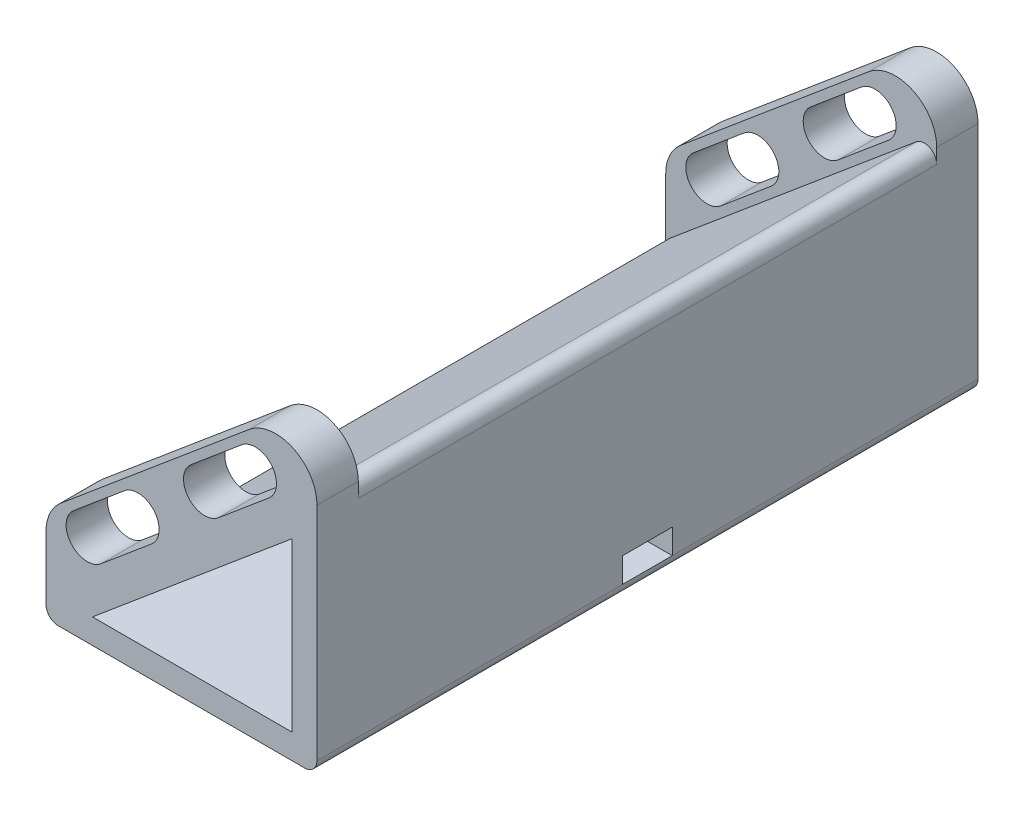
SolidWorks part; units mm, degrees
ref_plane "Front Plane" through (0, 0, 0) normal (0, 0, 1) x (1, 0, 0)
ref_plane "Top Plane" through (0, 0, 0) normal (0, 1, 0) x (1, 0, 0)
ref_plane "Right Plane" through (0, 0, 0) normal (1, 0, 0) x (0, 0, -1)
sketch "Sketch1" plane through (0, 0, 0) normal (0, 0, 1) x (1, 0, 0)
  line L0 (0, 0) -> (29.7938, 25) construction
  line L1 (-0.9642, 1.1491) -> (28.8297, 26.1491)
  line L2 (0.9642, -1.1491) -> (30.758, 23.8509)
  line L3 (0, 0) -> (24.6714, 0) construction
  line L4 (0, 0) -> (29.7938, 0) construction
  line L5 (0, 1.5) -> (29.7938, 1.5)
  line L6 (0, -1.5) -> (29.7938, -1.5)
  line L7 (29.7938, 25) -> (29.7938, 0) construction
  line L8 (31.2938, 25) -> (31.2938, 0)
  line L9 (28.2938, 25) -> (28.2938, 0)
  arc A0 (-0.9642, 1.1491) -> (0.9642, -1.1491) centre (0, 0) ccw
  arc A1 (30.758, 23.8509) -> (28.8297, 26.1491) centre (29.7938, 25) ccw
  arc A2 (0, 1.5) -> (0, -1.5) centre (0, 0) ccw
  arc A3 (29.7938, -1.5) -> (29.7938, 1.5) centre (29.7938, 0) ccw
  arc A4 (31.2938, 25) -> (28.2938, 25) centre (29.7938, 25) ccw
  arc A5 (28.2938, 0) -> (31.2938, 0) centre (29.7938, 0) ccw
  point P3 (14.8969, 12.5)
  point P10 (14.8969, 0)
  point P16 (29.7938, 12.5)
  dimension "D2" = 1.5
  dimension "D1" = 25
  dimension "D3" = 40
extrude "Boss-Extrude1" add sketch "Sketch1" along normal mid plane 80 contours A5 L9 L5 L2 A0 L6 | A4 L1 A2 L5 L2 L9 | A3 L8 A1 L2 L9 L5 | L9 A5 A3 L5 | L5 A2 A0 L2 | A1 A4 L9 L2
sketch "Sketch5" plane through (0, 0, 40) normal (0, 0, 1) x (1, 0, 0)
  line L0 (-1.5, 0) -> (-1.5, 10)
  line L1 (-1.5, 10) -> (31.2938, 37.5173)
  line L2 (31.2938, 37.5173) -> (31.2938, 25)
  line L3 (-0.9642, 1.1491) -> (28.8297, 26.1491) construction
  line L4 (-1.5, 0) -> (31.2938, 25)
  arc A0 (-0.9642, 1.1491) -> (0, -1.5) centre (0, 0) ccw construction
  dimension "D1" = 10
extrude "Boss-Extrude2" add sketch "Sketch5" against normal blind 5
fillet "Fillet1" radius 5 2 edges at (-1.5, 10, 37.5) (31.2938, 37.5173, 37.5)
sketch "Sketch7" plane through (0, 0, 40) normal (0, 0, 1) x (1, 0, 0)
  line L0 (3.5, 9.5452) -> (9.6284, 14.6875) construction
  line L1 (1.853, 11.5081) -> (7.9813, 16.6504)
  line L2 (5.147, 7.5824) -> (11.2754, 12.7247)
  line L3 (4.2744, 14.8453) -> (8.854, 9.3875) construction
  line L4 (-1.5, 7.6685) -> (-1.5, 0)
  line L5 (23.0799, 30.625) -> (0.2861, 11.4987)
  line L6 (31.2938, 25) -> (31.2938, 26.7948)
  line L7 (-0.9642, 1.1491) -> (28.8297, 26.1491)
  line L8 (-1.5, 7.6685) -> (-1.5, 0) construction
  line L9 (23.0799, 30.625) -> (0.2861, 11.4987) construction
  line L10 (31.2938, 25) -> (31.2938, 26.7948) construction
  line L11 (-0.9642, 1.1491) -> (28.8297, 26.1491) construction
  line L12 (3.5, 9.5452) -> (23.8297, 26.6038) construction
  line L13 (13.6648, 18.0745) -> (11.375, 20.8034) construction
  line L14 (23.8297, 26.6038) -> (17.7013, 21.4615) construction
  line L15 (22.1826, 28.5667) -> (16.0543, 23.4244)
  line L16 (25.4767, 24.641) -> (19.3483, 19.4987)
  arc A0 (1.853, 11.5081) -> (5.147, 7.5824) centre (3.5, 9.5452) ccw
  arc A1 (11.2754, 12.7247) -> (7.9813, 16.6504) centre (9.6284, 14.6875) ccw
  arc A2 (22.1826, 28.5667) -> (25.4767, 24.641) centre (23.8297, 26.6038) cw
  arc A3 (19.3483, 19.4987) -> (16.0543, 23.4244) centre (17.7013, 21.4615) cw
  arc A4 (0.2861, 11.4987) -> (-1.5, 7.6685) centre (3.5, 7.6685) ccw
  arc A5 (31.2938, 26.7948) -> (23.0799, 30.625) centre (26.2938, 26.7948) ccw
  arc A6 (31.2938, 25) -> (28.8297, 26.1491) centre (29.7938, 25) ccw
  arc A7 (-0.9642, 1.1491) -> (-1.5, 0) centre (0, 0) ccw
  arc A8 (0.2861, 11.4987) -> (-1.5, 7.6685) centre (3.5, 7.6685) ccw construction
  arc A9 (31.2938, 26.7948) -> (23.0799, 30.625) centre (26.2938, 26.7948) ccw construction
  arc A10 (31.2938, 25) -> (28.8297, 26.1491) centre (29.7938, 25) ccw construction
  arc A11 (-0.9642, 1.1491) -> (-1.5, 0) centre (0, 0) ccw construction
  point P12 (6.5642, 12.1164)
  point P21 (6.5642, 12.1164)
  point P27 (20.7655, 24.0327)
  dimension "D2" = 8
  dimension "D3" = 5
  dimension "D4" = 2
  dimension "D5" = 5
  dimension "D1" = 0
extrude "Cut-Extrude2" cut sketch "Sketch7" against normal through all both and the other way through all
mirror "Mirror1" about plane through (0, 0, 0) normal (0, 0, 1) of "Cut-Extrude2", "Fillet1", "Boss-Extrude2"
sketch "Sketch8" plane through (31.2938, 0, 0) normal (1, 0, 0) x (0, 0, -1)
  line L0 (-40, 0) -> (40, 0) construction
  line L1 (-3, 0) -> (3, 0)
  line L2 (-3, 0) -> (-3, 3)
  line L3 (-3, 3) -> (3, 3)
  line L4 (3, 0) -> (3, 3)
  dimension "D1" = 3
  dimension "D2" = 6
extrude "Cut-Extrude3" cut sketch "Sketch8" against normal blind 6
